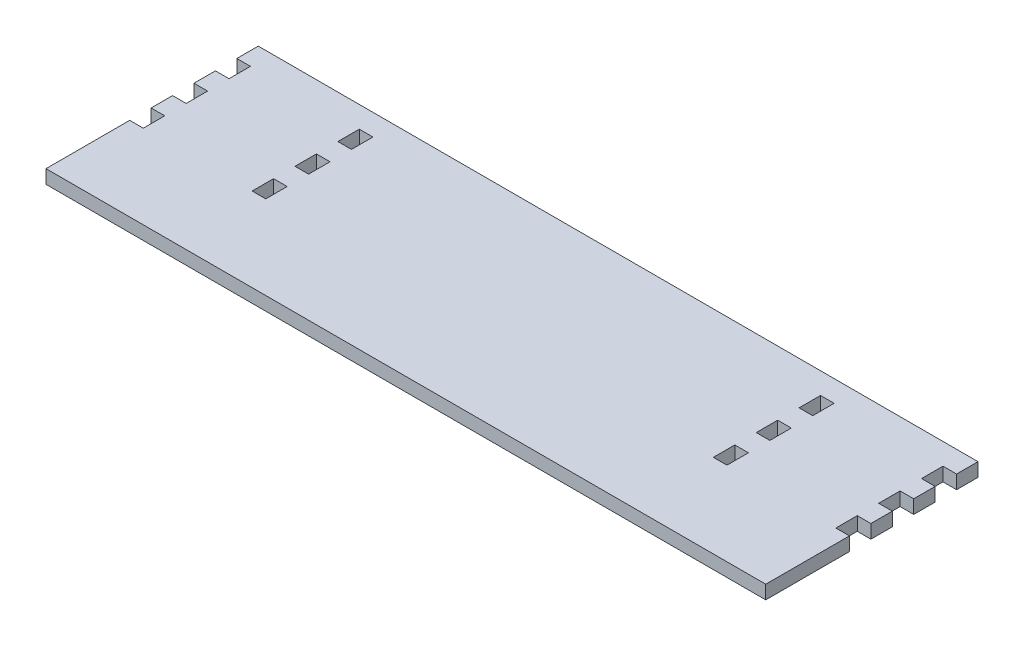
SolidWorks part; units mm, degrees
ref_plane "Front Plane" through (0, 0, 0) normal (0, 0, 1) x (1, 0, 0)
ref_plane "Top Plane" through (0, 0, 0) normal (0, 1, 0) x (1, 0, 0)
ref_plane "Right Plane" through (0, 0, 0) normal (1, 0, 0) x (0, 0, -1)
sketch "Sketch1" plane through (0, 0, 0) normal (0, 1, 0) x (1, 0, 0)
  line L0 (-167.9575, -5) -> (-164.7825, -5)
  line L1 (-66.4845, 0) -> (-164.7825, 0)
  line L2 (-136.2075, -5) -> (-136.2075, 0) construction
  line L3 (-66.4845, -49.53) -> (-164.7825, -49.53)
  line L4 (-167.9575, -30) -> (-167.9575, -49.53)
  line L5 (-3.175, -25) -> (-3.175, -30)
  line L6 (-167.9575, -5) -> (-167.9575, 0)
  line L7 (-167.9575, 0) -> (-164.7825, 0)
  line L8 (-167.9575, -10) -> (-164.7825, -10)
  line L9 (-3.175, -15) -> (-3.175, -20)
  line L10 (-3.175, -5) -> (-3.175, -10)
  line L11 (-164.7825, -15) -> (-167.9575, -15)
  line L12 (0, -20) -> (0, -25)
  line L13 (-167.9575, -20) -> (-164.7825, -20)
  line L14 (0, -10) -> (0, -15)
  line L15 (-164.7825, -25) -> (-167.9575, -25)
  line L16 (-167.9575, -49.53) -> (-164.7825, -49.53)
  line L17 (-167.9575, -30) -> (-164.7825, -30)
  line L18 (0, -30) -> (-3.175, -30)
  line L19 (-139.3825, -5) -> (-136.2075, -5)
  line L20 (0, -49.53) -> (-66.4845, -49.53)
  line L21 (-115.6335, 0) -> (-115.6335, -49.53) construction
  line L22 (-66.4845, 0) -> (0, 0)
  line L23 (0, 0) -> (0, -5) construction
  line L24 (-167.9575, -10) -> (-167.9575, -15)
  line L25 (-167.9575, -20) -> (-167.9575, -25)
  line L26 (-139.3825, -5) -> (-139.3825, -10)
  line L27 (-139.3825, -10) -> (-136.2075, -10)
  line L28 (0, -30) -> (-3.175, -30)
  line L29 (-3.175, -25) -> (0, -25)
  line L30 (-136.2075, -5) -> (-136.2075, -10)
  line L31 (0, -20) -> (-3.175, -20)
  line L32 (-139.3825, -15) -> (-136.2075, -15)
  line L33 (-3.175, -15) -> (0, -15)
  line L34 (-139.3825, -15) -> (-139.3825, -20)
  line L35 (-139.3825, -20) -> (-136.2075, -20)
  line L36 (0, -10) -> (-3.175, -10)
  line L37 (-136.2075, -15) -> (-136.2075, -20)
  line L38 (0, -5) -> (-3.175, -5)
  line L39 (-164.7825, -5) -> (-164.7825, -10)
  line L40 (-164.7825, -15) -> (-164.7825, -20)
  line L41 (-164.7825, -25) -> (-164.7825, -30)
  line L42 (-3.175, -25) -> (0, -25)
  line L43 (0, -20) -> (-3.175, -20)
  line L44 (-3.175, -15) -> (0, -15)
  line L45 (0, -10) -> (-3.175, -10)
  line L46 (0, 0) -> (-66.4845, 0) construction
  line L47 (0, -5) -> (0, 0)
  line L48 (0, -30) -> (0, -49.53)
  line L49 (0, -5) -> (-3.175, -5)
  line L50 (-139.3825, -25) -> (-136.2075, -25)
  line L51 (-139.3825, -25) -> (-139.3825, -30)
  line L52 (-139.3825, -30) -> (-136.2075, -30)
  line L53 (-136.2075, -25) -> (-136.2075, -30)
  line L54 (-136.2075, -10) -> (-136.2075, -15) construction
  line L55 (-136.2075, -20) -> (-136.2075, -25) construction
  line L56 (-31.75, -20) -> (-31.75, -25) construction
  line L57 (-31.75, -10) -> (-31.75, -15) construction
  line L58 (-31.75, -5) -> (-31.75, 0) construction
  line L59 (-31.75, -25) -> (-31.75, -30)
  line L60 (-28.575, -30) -> (-31.75, -30)
  line L61 (-28.575, -25) -> (-28.575, -30)
  line L62 (-28.575, -25) -> (-31.75, -25)
  line L63 (-31.75, -15) -> (-31.75, -20)
  line L64 (-28.575, -20) -> (-31.75, -20)
  line L65 (-28.575, -15) -> (-28.575, -20)
  line L66 (-28.575, -15) -> (-31.75, -15)
  line L67 (-31.75, -5) -> (-31.75, -10)
  line L68 (-28.575, -10) -> (-31.75, -10)
  line L69 (-28.575, -5) -> (-28.575, -10)
  line L70 (-28.575, -5) -> (-31.75, -5)
  dimension "D1" = 5
  dimension "D2" = 167.9575
  dimension "D3" = 3.175
  dimension "D4" = 5
  dimension "D5" = 49.53
  dimension "D6" = 5
  dimension "D7" = 5
  dimension "D8" = 3.175
  dimension "D9" = 25.4
  dimension "D10" = 3.175
  dimension "D11" = 3.175
  dimension "D12" = 25.4
extrude "Boss-Extrude1" add sketch "Sketch1" along normal blind 3.175 contours L48 L18 L5 L29 L12 L31 L9 L33 L14 L36 L10 L38 L47 L46 L1 L7 L6 L0 L39 L8 L24 L11 L40 L13 L25 L15 L41 L17 L4 L16 L3 L20
